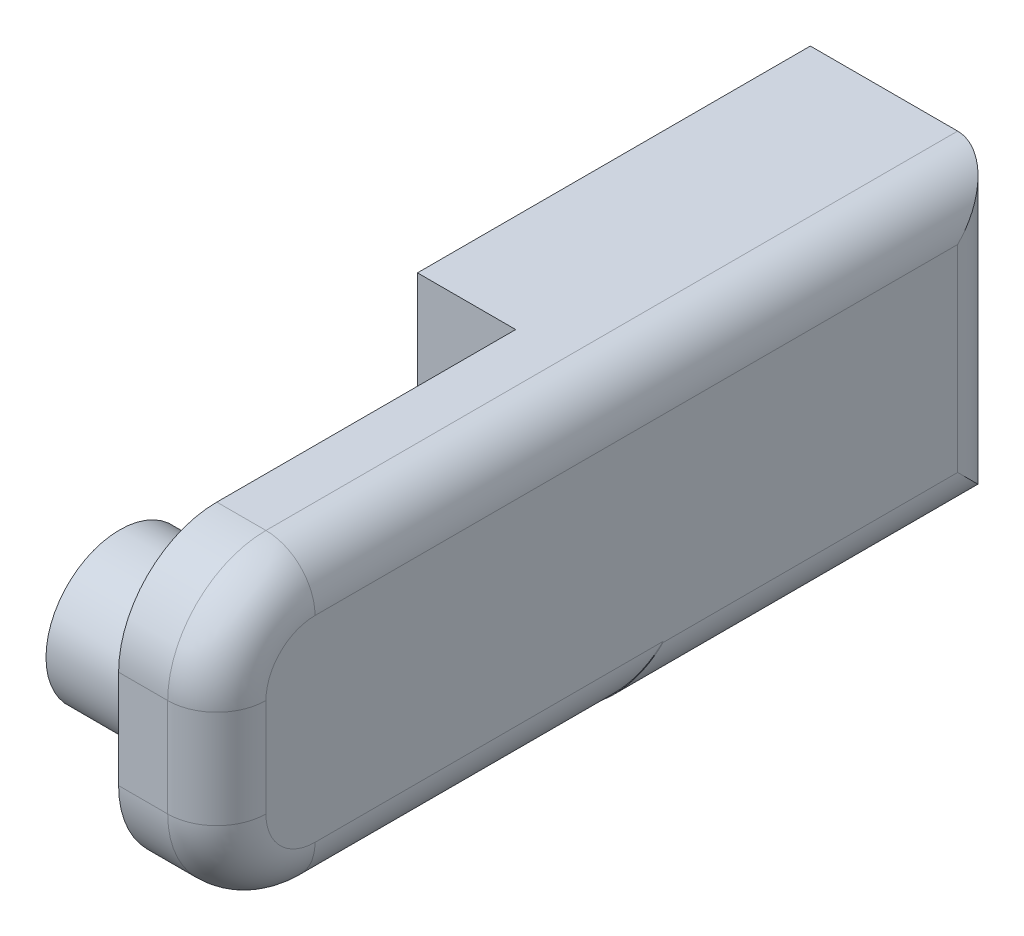
SolidWorks part; units mm, degrees
ref_plane "Front Plane" through (0, 0, 0) normal (0, 0, 1) x (1, 0, 0)
ref_plane "Top Plane" through (0, 0, 0) normal (0, 1, 0) x (1, 0, 0)
ref_plane "Right Plane" through (0, 0, 0) normal (1, 0, 0) x (0, 0, -1)
sketch "Sketch1" plane through (0, 0, 0) normal (1, 0, 0) x (0, 0, -1)
  line L1 (-20.2154, 15) -> (20.2154, 15)
  line L2 (-20.2154, 15) -> (-20.2154, -15)
  line L3 (-20.2154, -15) -> (20.2154, -15)
  line L4 (20.2154, 15) -> (20.2154, -15)
  line L5 (-20.2154, 15) -> (20.2154, -15) construction
  line L6 (-20.2154, -15) -> (20.2154, 15) construction
  point P0 (0, 0)
  dimension "D1" = 30
extrude "Boss-Extrude1" add sketch "Sketch1" along normal blind 10
sketch "Sketch2" plane through (0, 0, 0) normal (-1, 0, 0) x (0, 0, 1)
  line L0 (0, 0) -> (20.2154, 0) construction
  line L1 (20.2154, 15) -> (20.2154, -15) construction
  circle A0 centre (10.1077, 0) radius 7.5
  dimension "D1" = 15
extrude "Boss-Extrude2" add sketch "Sketch2" along normal blind 20
fillet "Fillet1" radius 10 2 edges at (5, -15, 20.2154) (5, 15, 20.2154)
sketch "Sketch3" plane through (-20, 0, 0) normal (-1, 0, 0) x (0, 0, 1)
  circle A0 centre (10.1077, 0) radius 7.5
extrude "Cut-Extrude1" cut sketch "Sketch3" against normal blind 10
sketch "Sketch4" plane through (0, 0, -20.2154) normal (0, 0, -1) x (-1, 0, 0)
  line L1 (-10, 15) -> (10, 15)
  line L2 (-10, 15) -> (-10, -15.1024)
  line L3 (-10, -15.1024) -> (10, -15.1024)
  line L4 (10, 15) -> (10, -15.1024)
  dimension "D1" = 20
extrude "Boss-Extrude3" add sketch "Sketch4" along normal blind 40
fillet "Fillet2" radius 5 8 edges at (10, 12.0711, 17.2865) (10, 15, -25) (10, -0.0512, -60.2154) (10, -15.1024, -40.2154) (10, -15.0512, -20.2154) (10, -15, -5) (10, -12.0711, 17.2865) (10, 0, 20.2154)
sketch "Sketch5" plane through (0, 0, -60.2154) normal (0, 0, -1) x (-1, 0, 0)
  line L0 (-5, 15) -> (10, -15.1024) construction
  circle A0 centre (2.5, -0.0512) radius 5
  dimension "D1" = 10
extrude "Cut-Extrude2" cut sketch "Sketch5" against normal blind 10
